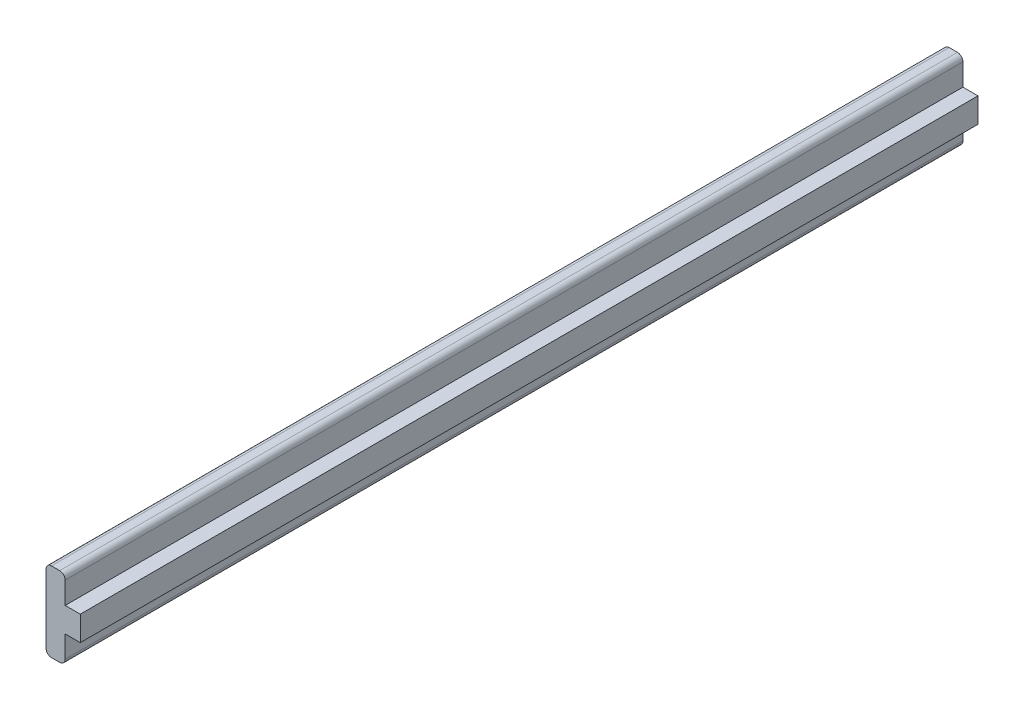
SolidWorks part; units mm, degrees
ref_plane "Front Plane" through (0, 0, 0) normal (0, 0, 1) x (1, 0, 0)
ref_plane "Top Plane" through (0, 0, 0) normal (0, 1, 0) x (1, 0, 0)
ref_plane "Right Plane" through (0, 0, 0) normal (1, 0, 0) x (0, 0, -1)
sketch "Sketch1" plane through (0, 0, 0) normal (0, 0, 1) x (1, 0, 0)
  line L0 (0, 0) -> (2, 0)
  line L1 (55, 0) -> (-55, 0) construction
  line L2 (2, 0) -> (2, 2)
  line L3 (2, 2) -> (3.5, 2)
  line L4 (3.5, 2) -> (3.5, -4)
  line L5 (3.5, -4) -> (2, -4)
  line L6 (2, -4) -> (2, -2)
  line L7 (2, -2) -> (0, -2)
  line L8 (0, -55) -> (0, 55) construction
  line L9 (0, -2) -> (0, -4)
  line L10 (0, -4) -> (-1.5, -4)
  line L11 (-1.5, -4) -> (-1.5, 2)
  line L12 (-1.5, 2) -> (0, 2)
  line L13 (0, 2) -> (0, 0)
extrude "Boss-Extrude1" add sketch "Sketch1" along normal blind 21
sketch "Sketch2" plane through (0, 0, 21) normal (0, 0, 1) x (1, 0, 0)
  line L0 (-1.5, 2) -> (-1.5, 1.9)
  line L1 (-1.5, 2) -> (-1.5, -4) construction
  line L2 (-1.5, 1.9) -> (-0.1, 1.9)
  line L3 (-0.1, 1.9) -> (-0.1, -0.1)
  line L4 (-0.1, -0.1) -> (2.1, -0.1)
  line L5 (1, -0.1) -> (1, 49999.9) construction
  line L6 (2.1, 1.9) -> (2.1, -0.1)
  line L7 (3.5, 1.9) -> (2.1, 1.9)
  line L8 (3.5, 2) -> (3.5, 1.9)
  line L9 (-1.5, 2) -> (3.5, 2)
  line L10 (-1.5, -1) -> (49998.5, -1) construction
  line L11 (-1.5, -4) -> (3.5, -4)
  line L12 (3.5, -4) -> (3.5, -3.9)
  line L13 (3.5, -3.9) -> (2.1, -3.9)
  line L14 (2.1, -3.9) -> (2.1, -1.9)
  line L15 (-0.1, -1.9) -> (2.1, -1.9)
  line L16 (-0.1, -3.9) -> (-0.1, -1.9)
  line L17 (-1.5, -3.9) -> (-0.1, -3.9)
  line L18 (-1.5, -4) -> (-1.5, -3.9)
  point P11 (1, -0.1)
  point P16 (-1.5, -1)
  point P25 (1, -1.9)
extrude "Cut-Extrude1" cut sketch "Sketch2" against normal through all
sketch "Sketch3" plane through (0, 0, 0) normal (0, 0, -1) x (-1, 0, 0)
  line L24 (-2.1, -0.1) -> (-2.1, 1.9)
  line L25 (-2.1, 1.9) -> (-3.5, 1.9)
  line L26 (-3.5, 1.9) -> (-3.5, -3.9)
  line L27 (-3.5, -3.9) -> (-2.1, -3.9)
  line L28 (-2.1, -3.9) -> (-2.1, -1.9)
  line L29 (-2.1, -1.9) -> (0.1, -1.9)
  line L30 (0.1, -1.9) -> (0.1, -3.9)
  line L31 (0.1, -3.9) -> (1.5, -3.9)
  line L32 (1.5, -3.9) -> (1.5, 1.9)
  line L33 (1.5, 1.9) -> (0.1, 1.9)
  line L34 (0.1, 1.9) -> (0.1, -0.1)
  line L35 (0.1, -0.1) -> (-2.1, -0.1)
  line L36 (-2.1, -0.1) -> (-2.1, 1.9)
  line L37 (-2.1, 1.9) -> (-3.5, 1.9)
  line L38 (-3.5, 1.9) -> (-3.5, -3.9)
  line L39 (-3.5, -3.9) -> (-2.1, -3.9)
  line L40 (-2.1, -3.9) -> (-2.1, -1.9)
  line L41 (-2.1, -1.9) -> (0.1, -1.9)
  line L42 (0.1, -1.9) -> (0.1, -3.9)
  line L43 (0.1, -3.9) -> (1.5, -3.9)
  line L44 (1.5, -3.9) -> (1.5, 1.9)
  line L45 (1.5, 1.9) -> (0.1, 1.9)
  line L46 (0.1, 1.9) -> (0.1, -0.1)
  line L47 (0.1, -0.1) -> (-2.1, -0.1)
  dimension "D1" = 0
extrude "Boss-Extrude2" add sketch "Sketch3" along normal blind 49
fillet "Fillet1" radius 0.4 8 edges at (-1.5, 1.9, -14) (-0.1, 1.9, -14) (-1.5, -3.9, -14) (-0.1, -3.9, -14) (2.1, -3.9, -14) (3.5, -3.9, -14) (3.5, 1.9, -14) (2.1, 1.9, -14)
sketch "Sketch4" plane through (0, 0, 21) normal (0, 0, 1) x (1, 0, 0)
  line L1 (-2.3353, 2.4707) -> (5.055, 2.4707)
  line L2 (-2.3353, 2.4707) -> (-2.3353, -4.4549)
  line L3 (-2.3353, -4.4549) -> (5.055, -4.4549)
  line L4 (5.055, 2.4707) -> (5.055, -4.4549)
extrude "Cut-Extrude2" cut sketch "Sketch4" against normal blind 4.5
sketch "Sketch5" plane through (0, 0, 16.5) normal (0, 0, 1) x (1, 0, 0)
  line L0 (1, -0.1) -> (1, -4.4713)
  line L1 (2.1, -0.1) -> (-0.1, -0.1) construction
  line L2 (1, -4.4713) -> (4.0369, -4.4713)
  line L3 (4.0369, -4.4713) -> (4.0369, 2.6423)
  line L4 (4.0369, 2.6423) -> (1, 2.6423)
  line L5 (1, 2.6423) -> (1, -0.1)
extrude "Cut-Extrude3" cut sketch "Sketch5" against normal through all
